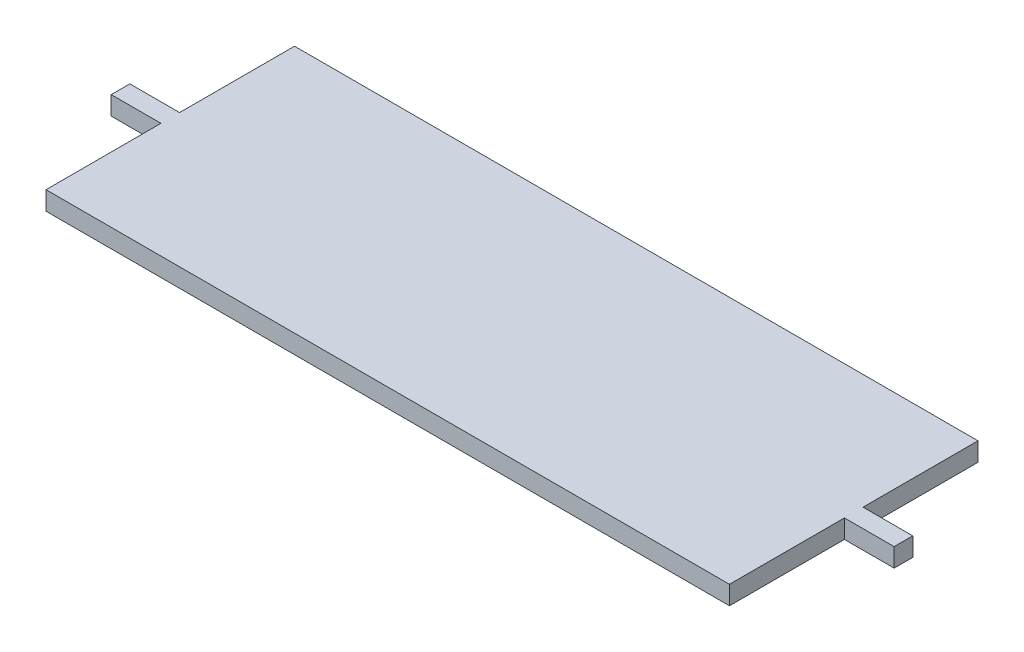
SolidWorks part; units mm, degrees
ref_plane "Front Plane" through (0, 0, 0) normal (0, 0, 1) x (1, 0, 0)
ref_plane "Top Plane" through (0, 0, 0) normal (0, 1, 0) x (1, 0, 0)
ref_plane "Right Plane" through (0, 0, 0) normal (1, 0, 0) x (0, 0, -1)
sketch "Sketch1" plane through (0, 0, 0) normal (0, 1, 0) x (1, 0, 0)
  line L0 (0, 0) -> (110, 0)
  line L1 (110, 0) -> (110, 40)
  line L2 (110, 40) -> (0, 40)
  line L3 (0, 40) -> (0, 0)
  line L4 (110, 20) -> (118, 20)
  line L5 (0, 20) -> (-8, 20)
  line L6 (-8, 20) -> (-8, 21.5)
  line L7 (-8, 20) -> (-8, 18.5)
  line L8 (-8, 21.5) -> (118, 21.5)
  line L9 (118, 21.5) -> (118, 18.5)
  line L10 (118, 18.5) -> (110, 18.5)
  line L11 (110, 18.5) -> (-8, 18.5)
  dimension "D1" = 110
  dimension "D2" = 40
  dimension "D3" = 8
  dimension "D4" = 8
  dimension "D5" = 1.5
  dimension "D6" = 1.5
extrude "Boss-Extrude1" add sketch "Sketch1" along normal blind 3 contours L8 L6 L5 L3 | L11 L3 L5 L7 | L11 L1 L8 L3 | L3 L8 L1 L2 | L1 L11 L3 L0 | L9 L8 L1 L4 | L10 L9 L4 L1
